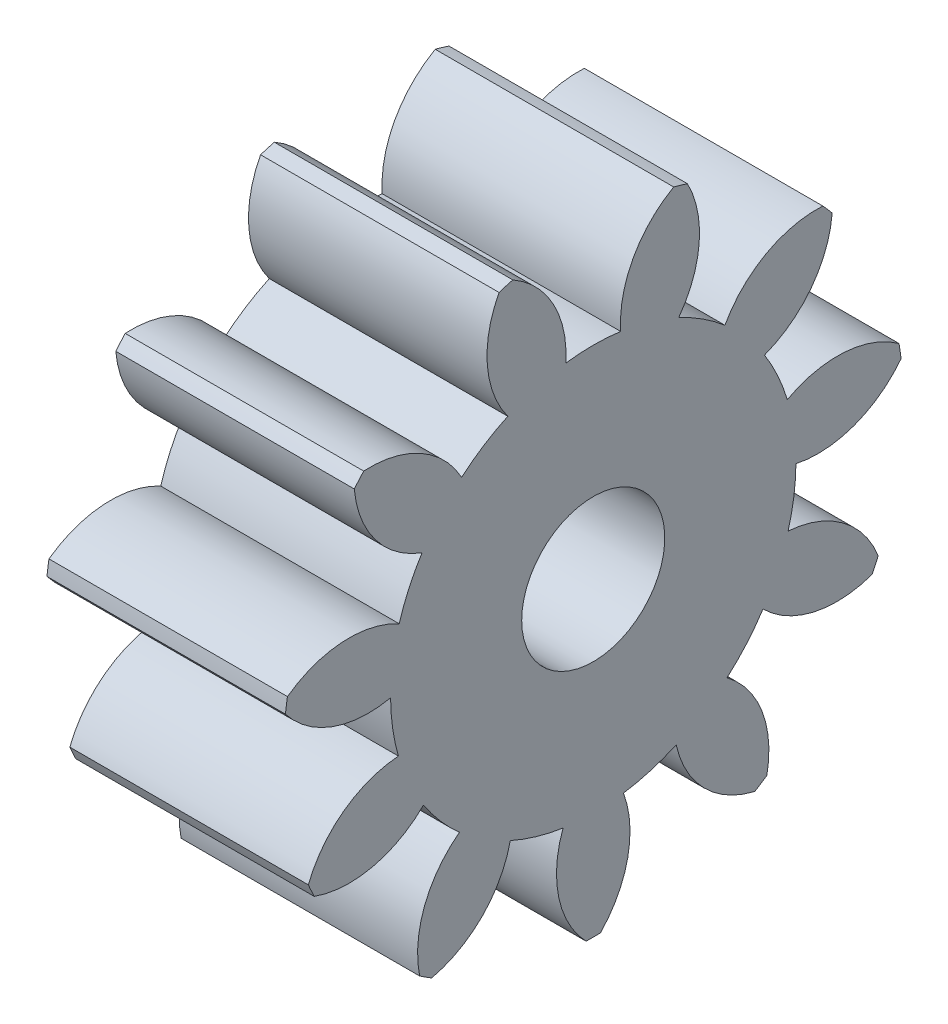
SolidWorks part; units mm, degrees
ref_plane "Plane1" through (0, 0, 0) normal (0, 0, 1) x (1, 0, 0)
ref_plane "Plane2" through (0, 0, 0) normal (0, 1, 0) x (1, 0, 0)
ref_plane "Plane3" through (0, 0, 0) normal (1, 0, 0) x (0, 0, -1)
sketch "HoldingSke" plane through (0, 0, 0) normal (0, 1, 0) x (1, 0, 0)
  line L0 (0, 0) -> (0.9816, -0.1908)
  line L1 (-15, 0) -> (100, 0) construction
  line L2 (0, 0) -> (-2.1039, 2.3779)
  line L3 (0, 0) -> (-11.863, 4.5341)
  line L4 (0, 0) -> (8.4773, 1.6478)
  line L5 (0, 0) -> (-46.8476, -17.4728)
  line L6 (0, 0) -> (-4.1448, -2.7965)
  line L7 (-2.1039, 2.3779) -> (8.6586, 51.2059)
  line L8 (-76.2, 54.61) -> (-75.7, 54.61)
  line L9 (-71.009, 38.7566) -> (-53.1078, 45.2721)
  line L10 (-76.2, 71.12) -> (104.1128, 71.12)
  line L11 (0, 0) -> (-5, 0)
  line L12 (-76.2, 101.6) -> (-76.162, 101.6)
  line L13 (24.9733, 27.94) -> (52.9518, 28.4284)
  line L14 (24.9733, 27.94) -> (24.9743, 27.94)
  line L15 (24.9733, 27.94) -> (100.4006, 29.5858)
  line L16 (-63.627, -1) -> (-12.827, -1)
  circle A0 centre (0, 0) radius 1.5
  circle A1 centre (0, 0) radius 4.249
  circle A2 centre (0, 0) radius 37.5
  circle A3 centre (0, 0) radius 1.5
  dimension "MHD" = 8.498
  dimension "Hub_dia" = 75
  dimension "Bore" = 3
  dimension "MBD" = 3
  dimension "Num_teeth" = 11
  dimension "Pitch" = 1
  dimension "Overall_len" = 50
  dimension "Show_teeth" = 11
  dimension "Thickness" = 5
  dimension "OAL" = 50.0001
  dimension "T_dim" = 0.5
  dimension "Ap" = 20
  dimension "H" = 19.05
  dimension "Pitch_radius" = 180.3128
  dimension "Width" = 5
  dimension "Backlash" = 0.038
  dimension "Addendum_fac" = 1
  dimension "Dedendum_fac" = 1.25
  dimension "Clearance_fac" = 0.25
  dimension "Dedendum_add" = 0.001
  dimension "Module" = 1
sketch "BasProSke" plane through (0, 0, 0) normal (0, 1, 0) x (1, 0, 0)
  line L0 (-10, 0) -> (60, 0) construction
  line L1 (0, 0) -> (0, 6.5)
  line L2 (0, 0) -> (5, 0)
  line L3 (5, 0) -> (5, 6.5)
  line L4 (5, 6.5) -> (0, 6.5)
  dimension "Thickness" = 5
  dimension "Diameter" = 13
revolve "Base-Revolve" add sketch "BasProSke" angle 360 about L0
sketch "TooCutSke" plane through (0, 0, 0) normal (1, 0, 0) x (0, 0, -1)
  line L1 (0, 0) -> (0, 107) construction
  line L2 (0, 0) -> (-0.8491, 5.4341) construction
  line L3 (0, 0) -> (-3.0727, 10.4645) construction
  line L4 (-0.8491, 5.4341) -> (-1.5363, 5.2323) construction
  arc A0 (0.576, 4.2098) -> (-0.576, 4.2098) centre (0, 0) ccw
  arc A1 (1.7187, 6.295) -> (-1.7187, 6.295) centre (0, 0) ccw
  circle A2 centre (0, 0) radius 5.5 construction
  circle A3 centre (0, 0) radius 5.1683 construction
  arc A4 (-0.576, 4.2098) -> (-1.7187, 6.295) centre (-2.7707, 4.3629) ccw
  arc A5 (1.7187, 6.295) -> (0.576, 4.2098) centre (2.7707, 4.3629) ccw
  dimension "Root_dia" = 8.498
  dimension "Overcut_dia" = 13.0508
  dimension "Pitch_dia" = 11
  dimension "Base_dia" = 10.3366
  dimension "Flank_rad" = 2.2
  dimension "Half_ang" = 16.364
  dimension "Half_CT" = 0.7162
extrude "ToothCut" cut sketch "TooCutSke" along normal through all
fillet "Breaks" [suppressed] radius 0.02
fillet "RootFillets" [suppressed] radius 0.251
pattern_circular "TeethCuts" count 11 every 32.727 about axis through (-10, 0, 0) along (1, 0, 0) of "ToothCut", "RootFillets", "Breaks"
sketch "HubNeaOneSke" plane through (0, 0, 0) normal (-1, 0, 0) x (0, 0, 1)
  circle A0 centre (0, 0) radius 4.249
  dimension "Diameter" = 8.498
extrude "HubNearOne" [suppressed] add sketch "HubNeaOneSke" along normal blind 45.0001
sketch "HubNeaBotSke" plane through (0, 0, 0) normal (-1, 0, 0) x (0, 0, 1)
  circle A0 centre (0, 0) radius 4.249
  dimension "Diameter" = 8.498
extrude "HubNearBoth" [suppressed] add sketch "HubNeaBotSke" along normal blind 22.5
ref_plane "FarPln" through (5, 0, 0) normal (1, 0, 0) x (0, 0, -1)
sketch "HubFarSke" plane through (5, 0, 0) normal (1, 0, 0) x (0, 0, -1)
  circle A0 centre (0, 0) radius 4.249
  dimension "Diameter" = 8.498
extrude "HubFar" [suppressed] add sketch "HubFarSke" along normal blind 22.5
sketch "BorSke" plane through (0, 0, 0) normal (1, 0, 0) x (0, 0, -1)
  circle A0 centre (0, 0) radius 1.5
  dimension "Diameter" = 3
extrude "Bore" cut sketch "BorSke" along normal mid plane 100.0001
sketch "KeySke" plane through (0, 0, 0) normal (1, 0, 0) x (0, 0, -1)
  line L0 (-0.6, 0) -> (-0.6, 2)
  line L1 (-0.6, 2) -> (0.6, 2)
  line L2 (0.6, 2) -> (0.6, 0)
  line L3 (0, 0) -> (0, 34) construction
  line L4 (-0.6, 0) -> (0.6, 0)
  dimension "Offset" = 2
  dimension "Width" = 1.2
extrude "Keyway" [suppressed] cut sketch "KeySke" along normal mid plane 100.0001
pattern_circular "Keyway2" [suppressed] count 2 every 90 about axis through (-10, 0, 0) along (1, 0, 0)
sketch "Esquisse1" plane through (0, 0, 0) normal (-1, 0, 0) x (0, 0, 1)
  circle A0 centre (0, 0) radius 2.75
  dimension "D1" = 5.5
extrude "Enlèv. mat.-Extru.1" cut sketch "Esquisse1" against normal blind 3
sketch "Esquisse2" plane through (3, 0, 0) normal (-1, 0, 0) x (0, 0, 1)
  circle A0 centre (0, 0) radius 1.5
  circle A1 centre (0, 0) radius 2.75
extrude "Boss.-Extru.1" add sketch "Esquisse2" along normal up to surface (3 mm away) up to face at (0, 0, 2.75)
sketch "Esquisse3" plane through (0, 0, 0) normal (-1, 0, 0) x (0, 0, 1)
  line L1 (2.3814, -2.1868) -> (3.0845, 0.969)
  line L2 (3.0845, 0.969) -> (0.7031, 3.1558)
  line L3 (0.7031, 3.1558) -> (-2.3814, 2.1868)
  line L4 (-2.3814, 2.1868) -> (-3.0845, -0.969)
  line L5 (-3.0845, -0.969) -> (-0.7031, -3.1558)
  line L6 (-0.7031, -3.1558) -> (2.3814, -2.1868)
  circle A0 centre (0, 0) radius 2.8 construction
  dimension "D1" = 5.6
extrude "Enlèv. mat.-Extru.2" cut sketch "Esquisse3" against normal blind 2
equation "' \"Module@HoldingSke\" = 6.35"
equation "' \"Num_teeth@HoldingSke\" = 12"
equation "' \"Ap@HoldingSke\" =  20"
equation "' \"Ap@HoldingSke\" = 20"
equation "' \"Width@HoldingSke\" = 0.5 * 25.4"
equation "' \"Hub_dia@HoldingSke\"= 1 * 25.4"
equation "' \"Hub_dia@HoldingSke\" = 1 * 25.4"
equation "' \"Overall_len@HoldingSke\" = 1.0 * 25.4"
equation "' \"Bore@HoldingSke\" = 0.75 * 25.4"
equation "' \"T_dim@HoldingSke\" = 0.1 * 25.4"
equation "' \"Width@KeySke\" = 0.25 * 25.4"
equation "' \"Show_teeth@HoldingSke\" = 13"
equation "' \"Backlash@HoldingSke\" = 0.009 * 25.4"
equation "' \"Addendum_fac@HoldingSke\" = 1.0"
equation "' \"Dedendum_fac@HoldingSke\" = 1.25"
equation "' \"Dedendum_add@HoldingSke\" = 0.00005 * 25.4"
equation "' \"Clearance_fac@HoldingSke\" = 0.25"
equation "\"Pitch@HoldingSke\" = 1 / \"Module@HoldingSke\""
equation "\"Overcut_dia@TooCutSke\" = (\"Num_teeth@HoldingSke\" + 2 * \"Addendum_fac@HoldingSke\") / \"Pitch@HoldingSke\" + 0.002 * 25.4"
equation "\"Pitch_dia@TooCutSke\" = \"Num_teeth@HoldingSke\" / \"Pitch@HoldingSke\""
equation "\"Base_dia@TooCutSke\" = \"Num_teeth@HoldingSke\" / \"Pitch@HoldingSke\" * cos((\"Ap@HoldingSke\"  * 3.14159265 / 180))"
equation "\"Root_dia@TooCutSke\" = (\"Num_teeth@HoldingSke\" + 2) / \"Pitch@HoldingSke\" - 2 * (\"Addendum_fac@HoldingSke\" + \"Dedendum_fac@HoldingSke\") / \"Pitch@HoldingSke\" - \"Dedendum_add@HoldingSke\" * 2"
equation "\"Half_ang@TooCutSke\" = 180 / \"Num_teeth@HoldingSke\""
equation "\"Half_CT@TooCutSke\" = \"Num_teeth@HoldingSke\" / \"Pitch@HoldingSke\" * sin((3.14159265 / 2 / \"Num_teeth@HoldingSke\")) / 2 - 7 * \"Backlash@HoldingSke\" / 4"
equation "\"Flank_rad@TooCutSke\" = \"Num_teeth@HoldingSke\" / \"Pitch@HoldingSke\" / 5"
equation "\"Radius@RootFillets\" = \"Clearance_fac@HoldingSke\" / \"Pitch@HoldingSke\" + \"Dedendum_add@HoldingSke\""
equation "\"Break_rad@Breaks\" = 0.02 / \"Pitch@HoldingSke\""
equation "\"Thickness@HoldingSke\" = \"Width@HoldingSke\""
equation "\"OAL@HoldingSke\" = \"Thickness@HoldingSke\""
equation "\"MHD@HoldingSke\" = (\"Num_teeth@HoldingSke\" + 2) / \"Pitch@HoldingSke\" - 2 * (\"Addendum_fac@HoldingSke\" + \"Dedendum_fac@HoldingSke\")  / \"Pitch@HoldingSke\" - \"Dedendum_add@HoldingSke\" * 2"
equation "\"MBD@HoldingSke\" = (\"Num_teeth@HoldingSke\" + 2) / \"Pitch@HoldingSke\" - 2 * (\"Addendum_fac@HoldingSke\" + \"Dedendum_fac@HoldingSke\")  / \"Pitch@HoldingSke\" - \"Dedendum_add@HoldingSke\" * 2 - 0.002 * 25.4"
equation "\"MHD@HoldingSke\" = ((sgn( \"MHD@HoldingSke\" - \"Hub_dia@HoldingSke\" )-1)*( \"MHD@HoldingSke\" - \"Hub_dia@HoldingSke\" ))/-2+ \"Hub_dia@HoldingSke\""
equation "\"MBD@HoldingSke\" = ((sgn( \"MBD@HoldingSke\" - \"Bore@HoldingSke\" )-1)*( \"MBD@HoldingSke\" - \"Bore@HoldingSke\" ))/-2+ \"Bore@HoldingSke\""
equation "\"OAL@HoldingSke\" = ((sgn( \"OAL@HoldingSke\" - \"Overall_len@HoldingSke\" )+1)*( \"OAL@HoldingSke\" - \"Overall_len@HoldingSke\" ))/2 + \"Overall_len@HoldingSke\" + 0.000002 * 25.4"
equation "\"Num_teeth@TeethCuts\" = int( \"Show_teeth@HoldingSke\" ) + 1"
equation "\"Num_teeth@TeethCuts\" = ((sgn( \"Num_teeth@TeethCuts\" - \"Num_teeth@HoldingSke\" )-1)*( \"Num_teeth@TeethCuts\" - \"Num_teeth@HoldingSke\" ))/-2+ \"Num_teeth@HoldingSke\""
equation "\"Num_teeth@TeethCuts\" = ((sgn( \"Num_teeth@TeethCuts\" - 2.0)+1)*( \"Num_teeth@TeethCuts\" - 2.0))/2 +2.0"
equation "\"Angle@TeethCuts\" = 360.0 / \"Num_teeth@HoldingSke\""
equation "\"Diameter@BasProSke\" = (\"Num_teeth@HoldingSke\" + 2 * \"Addendum_fac@HoldingSke\") / \"Pitch@HoldingSke\""
equation "\"Thickness@BasProSke\"  = \"Thickness@HoldingSke\""
equation "' \"Fillet_rad@BasProSke\" =  \"Thickness@HoldingSke\" * 0.05"
equation "' \"Fillet_rad@BasProSke\" = \"Thickness@HoldingSke\" * 0.05"
equation "\"MHD@HoldingSke\" = ((sgn( \"MHD@HoldingSke\" - \"Root_dia@TooCutSke\" )-1)*( \"MHD@HoldingSke\" - \"Root_dia@TooCutSke\" ))/-2+ \"Root_dia@TooCutSke\""
equation "\"Diameter@HubNeaOneSke\" = \"MHD@HoldingSke\""
equation "\"Length@HubNearOne\" = \"OAL@HoldingSke\" - \"Thickness@BasProSke\""
equation "\"Diameter@HubNeaBotSke\" = \"MHD@HoldingSke\""
equation "\"Length@HubNearBoth\" = ( \"OAL@HoldingSke\" - \"Thickness@BasProSke\" ) / 2.0"
equation "\"Thickness@FarPln\" = \"Thickness@BasProSke\""
equation "\"Diameter@HubFarSke\" = \"MHD@HoldingSke\""
equation "\"Length@HubFar\" = ( \"OAL@HoldingSke\" - \"Thickness@BasProSke\" ) / 2.0"
equation "\"Diameter@BorSke\" = \"MBD@HoldingSke\""
equation "\"D1@Bore\" = \"OAL@HoldingSke\" * 2.0"
equation "\"D1@Keyway\" = \"OAL@HoldingSke\" * 2.0"
equation "\"Offset@KeySke\" = \"T_dim@HoldingSke\" + \"MBD@HoldingSke\" / 2.0"
